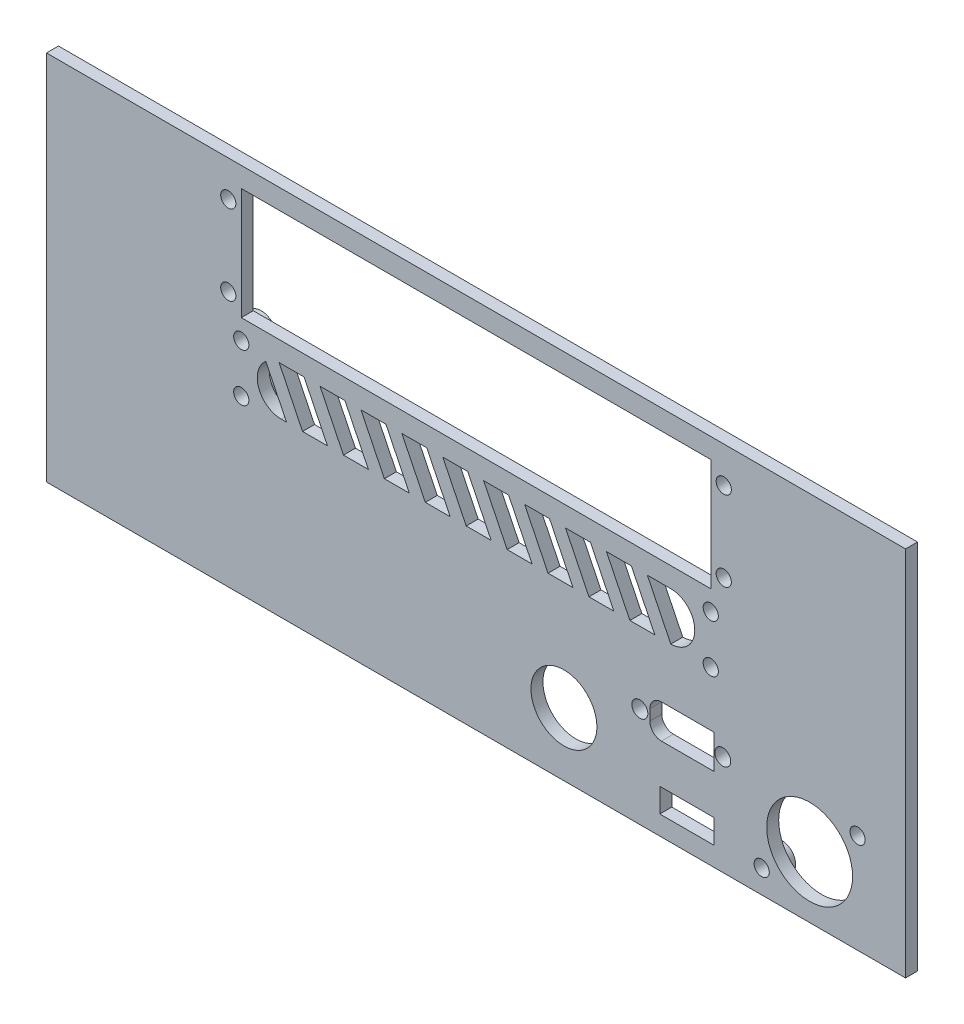
SolidWorks part; units mm, degrees
ref_plane "Płaszczyzna przednia" through (0, 0, 0) normal (0, 0, 1) x (1, 0, 0)
ref_plane "Płaszczyzna górna" through (0, 0, 0) normal (0, 1, 0) x (1, 0, 0)
ref_plane "Płaszczyzna prawa" through (0, 0, 0) normal (1, 0, 0) x (0, 0, -1)
sketch "Szkic1" plane through (0, 0, 0) normal (0, 0, 1) x (1, 0, 0)
  line L1 (0, 0) -> (215, 0)
  line L2 (0, 0) -> (0, 93)
  line L3 (0, 93) -> (215, 93)
  line L4 (215, 0) -> (215, 93)
  dimension "D1" = 215
  dimension "D2" = 93
extrude "Dodanie-wyciągnięcie1" add sketch "Szkic1" along normal blind 3
ref_plane "Płaszczyzna1" through (107.5, 0, 0) normal (1, 0, 0) x (0, 0, -1)
sketch "Szkic3" plane through (107.5, 0, 0) normal (1, 0, 0) x (0, 0, -1)
  line L0 (0, 3) -> (10, 3)
  line L1 (0, 41) -> (35, 41)
  line L2 (0, 0) -> (0, 93) construction
  line L3 (3, 11.5415) -> (3, 35)
  line L4 (3, 35) -> (31.193, 35)
  line L5 (35, 35) -> (35, 41)
  line L6 (0, 41) -> (0, 3)
  line L7 (9.7992, 7.6159) -> (3, 11.5415)
  line L8 (35, 35) -> (10, 3)
  line L9 (31.193, 35) -> (9.7992, 7.6159)
  dimension "D1" = 10
  dimension "D2" = 3
  dimension "D3" = 35
  dimension "D4" = 38
  dimension "D5" = 3
  dimension "D6" = 6
  dimension "D7" = 97.999
  dimension "D8" = 28.193
  dimension "D9" = 3
extrude "Dodanie-wyciągnięcie3" add sketch "Szkic3" along normal mid plane 10
sketch "Szkic4" plane through (0, 3, 0) normal (0, -1, 0) x (1, 0, 0)
  line L0 (102.5, 0) -> (102.5, -10) construction
  line L2 (112.5, -10) -> (102.5, -10) construction
  circle A0 centre (107.5, -5) radius 1.9
  dimension "D3" = 3.8
  dimension "D1" = 5
  dimension "D2" = 5
extrude "Wytnij-wyciągnięcie1" cut sketch "Szkic4" against normal blind 10
sketch "Szkic5" plane through (0, 0, 3) normal (0, 0, 1) x (1, 0, 0)
  line L0 (215, 93) -> (0, 93) construction
  line L1 (48.75, 88) -> (166.25, 88)
  line L2 (48.75, 88) -> (48.75, 60)
  line L3 (48.75, 60) -> (166.25, 60)
  line L4 (166.25, 88) -> (166.25, 60)
  line L5 (107.5, 93) -> (107.5, 105.9064) construction
  line L6 (48.75, 74) -> (107.5, 74) construction
  circle A0 centre (45.5, 84) radius 1.9
  circle A2 centre (45.5, 64) radius 1.9
  circle A3 centre (169.5, 64) radius 1.9
  circle A4 centre (169.5, 84) radius 1.9
  point P6 (107.5, 88)
  dimension "D6" = 3.8
  dimension "D4" = 20
  dimension "D1" = 5
  dimension "D2" = 28
  dimension "D3" = 117.5
  dimension "D5" = 62
extrude "Wytnij-wyciągnięcie2" cut sketch "Szkic5" against normal blind 35 contours A0 | A2 | A3 | A4 | L2 L3 L4 L1
chamfer "Sfazowanie1" distance 2 angle 45 3 edges at (107.5, 7.6159, -9.7992) (107.5, 35, -31.193) (107.5, 35, -3)
sketch "Szkic6" plane through (0, 0, 3) normal (0, 0, 1) x (1, 0, 0)
  line L1 (153.5, 10.8) -> (167, 10.8)
  line L2 (153.5, 10.8) -> (153.5, 4.8)
  line L3 (153.5, 4.8) -> (167, 4.8)
  line L4 (167, 10.8) -> (167, 4.8)
  line L10 (215, 0) -> (215, 93) construction
  line L11 (0, 0) -> (215, 0) construction
  line L13 (167, 20.8) -> (153.9, 20.8)
  line L14 (167, 20.8) -> (167, 29.3)
  line L15 (167, 29.3) -> (153.9, 29.3)
  line L16 (151, 23.7) -> (151, 26.4)
  circle A0 centre (191, 15.35) radius 10.75
  circle A1 centre (203, 24.85) radius 1.9
  circle A2 centre (179, 5.85) radius 1.9
  arc A3 (153.9, 20.8) -> (151, 23.7) centre (153.9, 23.7) cw
  arc A4 (153.9, 29.3) -> (151, 26.4) centre (153.9, 26.4) ccw
  circle A5 centre (148.5, 25.05) radius 2
  circle A6 centre (169.25, 25.05) radius 2
  point P16 (151, 20.8)
  dimension "D9" = 3.8
  dimension "D10" = 3.8
  dimension "D15" = 21.5
  dimension "D16" = 2.9
  dimension "D21" = 4
  dimension "D22" = 4
  dimension "D3" = 8.5
  dimension "D4" = 16
  dimension "D1" = 48
  dimension "D2" = 13.5
  dimension "D5" = 6
  dimension "D6" = 4.8
  dimension "D7" = 24
  dimension "D8" = 15.35
  dimension "D11" = 12
  dimension "D12" = 9.5
  dimension "D13" = 12
  dimension "D14" = 9.5
  dimension "D17" = 24
  dimension "D18" = 10
  dimension "D19" = 2.5
  dimension "D20" = 2.25
extrude "Wytnij-wyciągnięcie3" cut sketch "Szkic6" against normal through all
sketch "Szkic8" plane through (0, 0, 0) normal (0, 0, -1) x (-1, 0, 0)
  circle A0 centre (-179, 5.85) radius 3.5
  circle A1 centre (-203, 24.85) radius 3.5
  circle A2 centre (-203, 24.85) radius 2
  circle A3 centre (-179, 5.85) radius 2
  dimension "D1" = 7
  dimension "D2" = 7
  dimension "D3" = 4
  dimension "D4" = 4
extrude "Dodanie-wyciągnięcie4" add sketch "Szkic8" along normal blind 2
sketch "Szkic9" plane through (0, 0, 0) normal (0, 0, -1) x (-1, 0, 0)
  line L0 (-156.25, 49) -> (-58.75, 49) construction
  line L1 (-156.25, 55) -> (-58.75, 55)
  line L2 (-156.25, 43) -> (-58.75, 43)
  line L3 (-166.25, 60) -> (-48.75, 60) construction
  line L4 (-166.25, 60) -> (-166.25, 88) construction
  line L5 (-48.75, 60) -> (-48.75, 88) construction
  line L6 (-156.25, 43) -> (-150.385, 55)
  line L7 (-152.25, 43) -> (-146.385, 55)
  line L8 (-146.0097, 43) -> (-140.1447, 55)
  line L9 (-142.0097, 43) -> (-136.1447, 55)
  line L10 (-135.7694, 43) -> (-129.9045, 55)
  line L11 (-131.7694, 43) -> (-125.9045, 55)
  line L12 (-125.5292, 43) -> (-119.6642, 55)
  line L13 (-121.5292, 43) -> (-115.6642, 55)
  line L14 (-115.2889, 43) -> (-109.4239, 55)
  line L15 (-111.2889, 43) -> (-105.4239, 55)
  line L16 (-105.0486, 43) -> (-99.1836, 55)
  line L17 (-101.0486, 43) -> (-95.1836, 55)
  line L18 (-94.8083, 43) -> (-88.9434, 55)
  line L19 (-90.8083, 43) -> (-84.9434, 55)
  line L20 (-84.5681, 43) -> (-78.7031, 55)
  line L21 (-80.5681, 43) -> (-74.7031, 55)
  line L22 (-74.3278, 43) -> (-68.4628, 55)
  line L23 (-70.3278, 43) -> (-64.4628, 55)
  line L24 (-64.0875, 43) -> (-58.2225, 55)
  line L25 (-61.688, 39.7253) -> (-54.9041, 53.6054)
  line L26 (-107.5, 41) -> (-107.5, 71.4956) construction
  line L28 (-112.5, 41) -> (-102.5, 41) construction
  line L29 (-107.5, 49) -> (-179.9248, 49) construction
  arc A0 (-156.25, 55) -> (-156.25, 43) centre (-156.25, 49) ccw
  arc A1 (-58.75, 43) -> (-58.75, 55) centre (-58.75, 49) ccw
  circle A2 centre (-166.25, 55) radius 1.9
  circle A3 centre (-166.25, 43) radius 1.9
  circle A4 centre (-48.75, 43) radius 1.9
  circle A5 centre (-48.75, 55) radius 1.9
  point P2 (-107.5, 49)
  dimension "D7" = 3.8
  dimension "D1" = 11
  dimension "D2" = 10
  dimension "D3" = 10
  dimension "D4" = 12
  dimension "D5" = 4
  dimension "D8" = 6
  dimension "D9" = 10
  dimension "D6" = 10
extrude "Wytnij-wyciągnięcie4" cut sketch "Szkic9" against normal blind 3 contours A2 | A3 | L1 A0 L6 | L2 L8 L1 L7 | L2 L10 L1 L9 | L2 L12 L1 L11 | L2 L14 L1 L13 | L2 L16 L1 L15 | L2 L18 L1 L17 | L2 L20 L1 L19 | L2 L22 L1 L21 | L2 L24 L1 L23 | L2 A1 L25 | A4 | A5
sketch "Szkic10" plane through (0, 0, 0) normal (0, 0, -1) x (-1, 0, 0)
  circle A0 centre (-166.25, 43) radius 1.9
  circle A2 centre (-166.25, 55) radius 1.9
  circle A3 centre (-48.75, 55) radius 1.9
  circle A4 centre (-48.75, 43) radius 1.9
  circle A5 centre (-166.25, 55) radius 4
  circle A6 centre (-166.25, 43) radius 4
  circle A7 centre (-48.75, 43) radius 4
  circle A8 centre (-48.75, 55) radius 4
  dimension "D1" = 8
extrude "Dodanie-wyciągnięcie5" add sketch "Szkic10" along normal blind 2
sketch "Szkic11" plane through (0, 0, 0) normal (0, 0, -1) x (-1, 0, 0)
  line L0 (0, 0) -> (-215, 0) construction
  line L1 (-112.5, 41) -> (-112.5, 3) construction
  circle A0 centre (-129.5, 15.8) radius 8.25
  dimension "D1" = 16.5
  dimension "D3" = 17
  dimension "D2" = 15.8
extrude "Wytnij-wyciągnięcie5" cut sketch "Szkic11" against normal blind 10
sketch "Sketch1" plane through (112.5, 0, 0) normal (1, 0, 0) x (0, 0, -1)
  line L5 (0, 41) -> (0, 3)
  line L6 (0, 3) -> (10, 3)
  line L7 (10, 3) -> (35, 35)
  line L8 (35, 35) -> (35, 41)
  line L9 (35, 41) -> (0, 41)
  line L10 (0, 41) -> (0, 3)
  line L11 (0, 3) -> (10, 3)
  line L12 (10, 3) -> (35, 35)
  line L13 (35, 35) -> (35, 41)
  line L14 (35, 41) -> (0, 41)
  dimension "D1" = 0
extrude "Cut-Extrude1" cut sketch "Sketch1" against normal up to next
